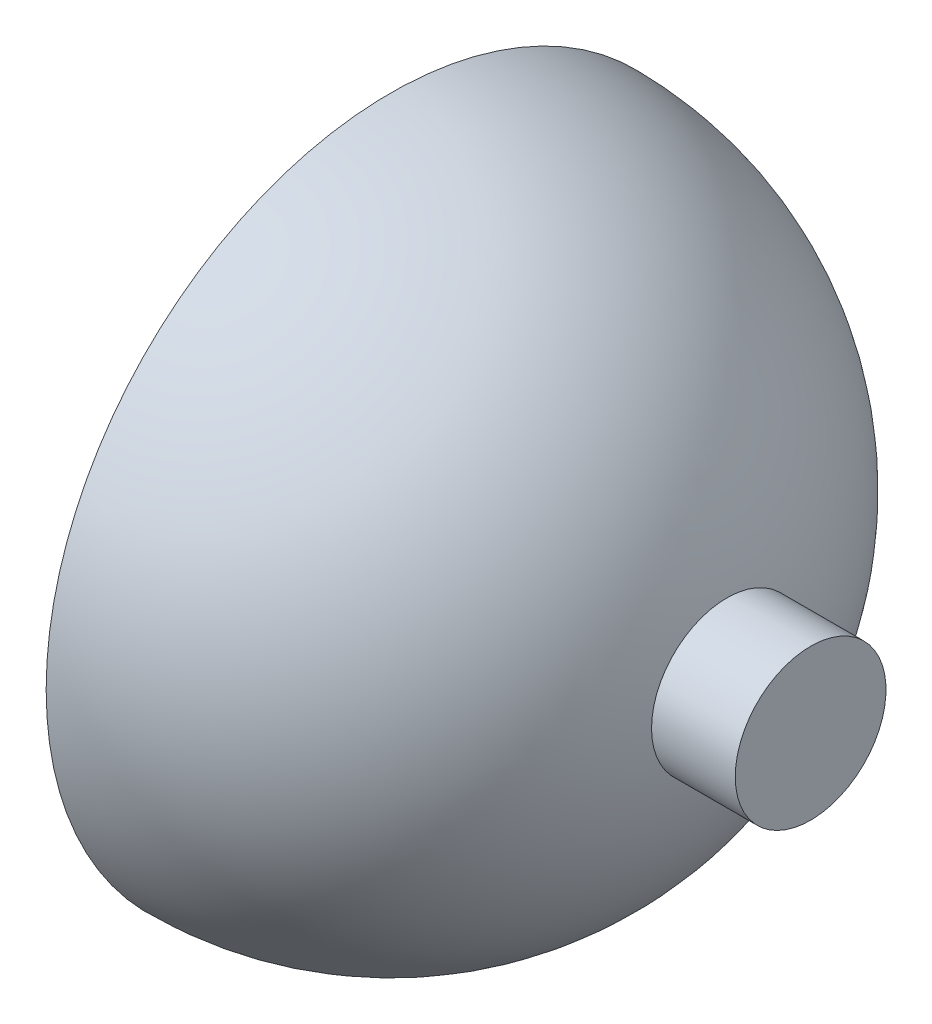
SolidWorks part; units mm, degrees
ref_plane "Front Plane" through (0, 0, 0) normal (0, 0, 1) x (1, 0, 0)
ref_plane "Top Plane" through (0, 0, 0) normal (0, 1, 0) x (1, 0, 0)
ref_plane "Right Plane" through (0, 0, 0) normal (1, 0, 0) x (0, 0, -1)
sketch "Sketch1" plane through (0, 0, 0) normal (0, 0, 1) x (1, 0, 0)
  line L0 (0, 0) -> (32, 0)
  line L5 (32, 0) -> (0, 0)
  line L6 (0, 32) -> (0, 0)
  line L7 (32, 0) -> (39, 0)
  line L8 (39, 0) -> (39, 7)
  line L9 (39, 7) -> (31.225, 7)
  arc A0 (31.225, 7) -> (0, 32) centre (0, 0) ccw
  arc A1 (28.38, 0) -> (0, 28.38) centre (0, 0) ccw
revolve "Revolve4" add sketch "Sketch1" angle 360 about L0
